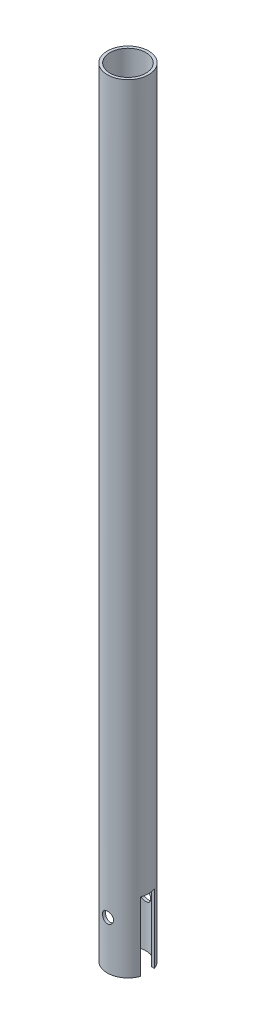
SolidWorks part; units mm, degrees
ref_plane "Спереди" through (0, 0, 0) normal (0, 0, 1) x (1, 0, 0)
ref_plane "Сверху" through (0, 0, 0) normal (0, 1, 0) x (1, 0, 0)
ref_plane "Справа" through (0, 0, 0) normal (1, 0, 0) x (0, 0, -1)
other "Configuration Table"
sketch "Sketch1" plane through (0, 0, 0) normal (0, 1, 0) x (1, 0, 0)
  circle A0 centre (0, 0) radius 15
  circle A1 centre (0, 0) radius 13
  dimension "D1" = 30
  dimension "D2" = 2
extrude "Boss-Extrude1" add sketch "Sketch1" along normal mid plane 565
sketch "Sketch3" plane through (0, 0, 0) normal (1, 0, 0) x (0, 0, -1)
  line L0 (-15, -282.5) -> (15, -282.5) construction
  line L1 (-5, -282.5) -> (5, -282.5)
  line L2 (-5, -282.5) -> (-5, -232.5)
  line L3 (-5, -232.5) -> (5, -232.5)
  line L4 (5, -282.5) -> (5, -232.5)
  line L6 (0, 308.2069) -> (0, -341.3903) construction
  dimension "D1" = 10
  dimension "D2" = 50
extrude "Cut-Extrude1" cut sketch "Sketch3" against normal mid plane 565
sketch "Sketch4" plane through (0, 0, 0) normal (0, 0, 1) x (1, 0, 0)
  line L0 (-14.1421, -282.5) -> (14.1421, -282.5) construction
  circle A0 centre (0, -247.5) radius 4
  dimension "D2" = 8
  dimension "D1" = 35
extrude "Cut-Extrude2" cut sketch "Sketch4" against normal through all both and the other way through all
